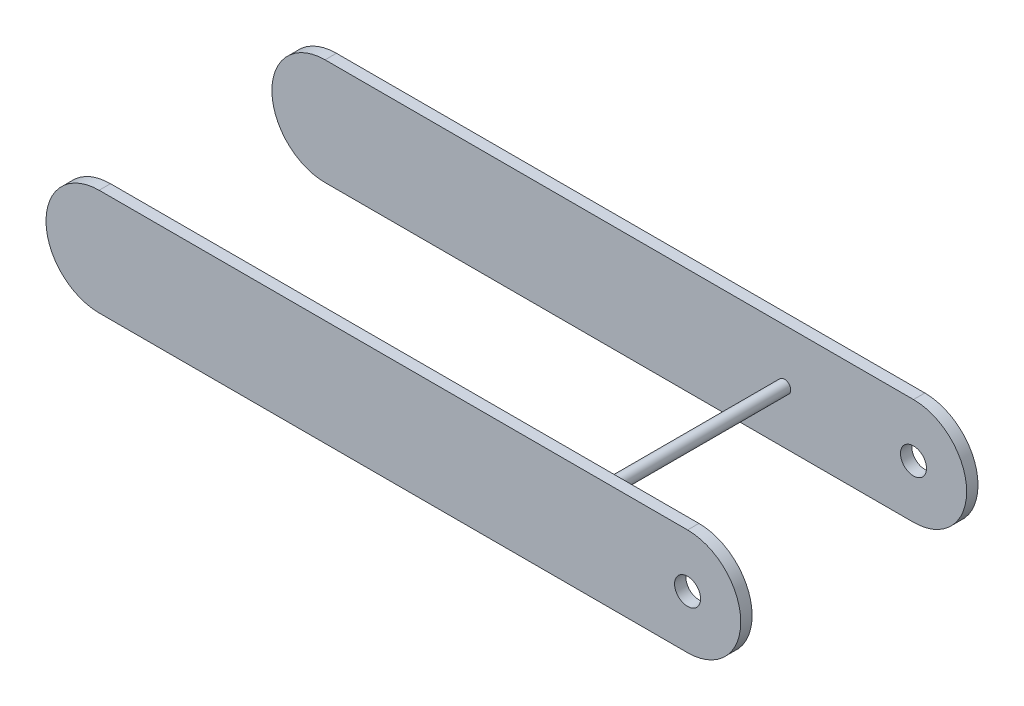
SolidWorks part; units mm, degrees
ref_plane "Front Plane" through (0, 0, 0) normal (0, 0, 1) x (1, 0, 0)
ref_plane "Top Plane" through (0, 0, 0) normal (0, 1, 0) x (1, 0, 0)
ref_plane "Right Plane" through (0, 0, 0) normal (1, 0, 0) x (0, 0, -1)
sketch "Sketch1" plane through (0, 0, 0) normal (0, 0, 1) x (1, 0, 0)
  line L0 (0, 0) -> (-149.5789, 0)
  line L1 (-149.5789, -50.6) -> (130.4211, -50.6)
  line L2 (130.4211, 0) -> (0, 0)
  arc A0 (-149.5789, 0) -> (-149.5789, -50.6) centre (-149.5789, -25.3) ccw
  arc A1 (130.4211, -50.6) -> (130.4211, 0) centre (130.4211, -25.3) ccw
  circle A2 centre (130.4211, -25.3) radius 6.2
  dimension "D1" = 280
  dimension "D3" = 12.4
  dimension "D2" = 50.6
extrude "Boss-Extrude1" add sketch "Sketch1" along normal blind 5.4
sketch "Sketch2" plane through (0, 0, 0) normal (0, 0, -1) x (-1, 0, 0)
  line L0 (-206.7904, -25.3) -> (233.7554, -25.3) construction
  line L1 (-155.4858, -25.3) -> (-68.9858, -25.3) construction
  circle A2 centre (-68.9858, -25.3) radius 3
  dimension "D1" = 86.5
  dimension "D2" = 6
extrude "Boss-Extrude3" add sketch "Sketch2" along normal blind 102.1
ref_plane "Plane1" through (0, 0, -102.1) normal (0, 0, -1) x (-1, 0, 0)
sketch "Sketch4" plane through (0, 0, -102.1) normal (0, 0, -1) x (-1, 0, 0)
  line L0 (-130.4211, 0) -> (149.5789, 0)
  line L1 (149.5789, -50.6) -> (-130.4211, -50.6)
  arc A0 (149.5789, 0) -> (149.5789, -50.6) centre (149.5789, -25.3) cw
  arc A1 (-130.4211, -50.6) -> (-130.4211, 0) centre (-130.4211, -25.3) cw
  circle A2 centre (-130.4211, -25.3) radius 6.2
  dimension "D1" = 12.4
extrude "Boss-Extrude4" add sketch "Sketch4" along normal blind 5.4
